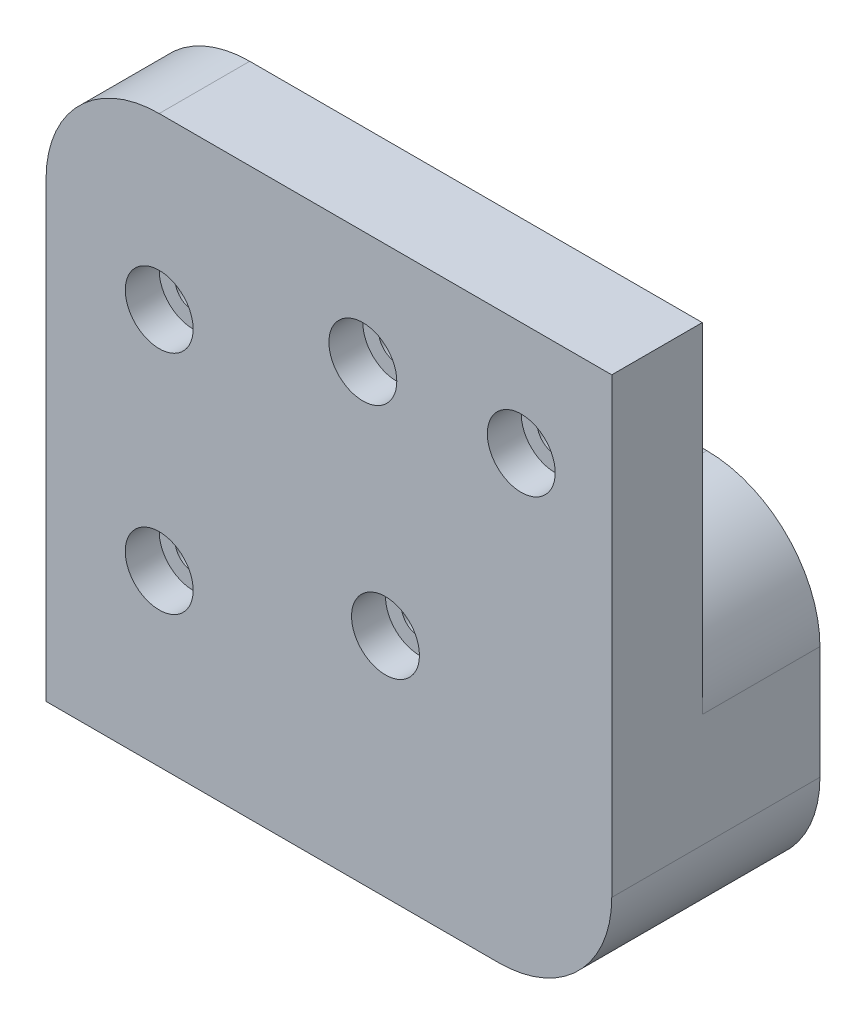
SolidWorks part; units mm, degrees
ref_plane "前视基准面" through (0, 0, 0) normal (0, 0, 1) x (1, 0, 0)
ref_plane "上视基准面" through (0, 0, 0) normal (0, 1, 0) x (1, 0, 0)
ref_plane "右视基准面" through (0, 0, 0) normal (1, 0, 0) x (0, 0, -1)
other "Configuration Table"
sketch "草图1" plane through (0, 0, 0) normal (0, 0, 1) x (1, 0, 0)
  line L0 (-10, 77.5) -> (-10, -160) construction
  line L2 (10, 57.5) -> (10, 27.5)
  line L3 (10, 27.5) -> (-10, 27.5)
  line L4 (-10, 77.5) -> (-10, 27.5)
  line L5 (-10, 77.5) -> (40, 77.5)
  line L7 (10, 57.5) -> (40, 57.5)
  line L8 (40, 77.5) -> (40, 57.5)
  line L9 (184.3942, 77.5) -> (10.0042, 77.5) construction
  line L10 (184.3942, 57.5) -> (10.0042, 57.5) construction
  line L11 (10, -130.0288) -> (10, 47.5288) construction
  circle A0 centre (32, 67.5) radius 1.6
  circle A1 centre (18, 67.5) radius 1.6
  circle A2 centre (0, 62.5) radius 1.6
  circle A3 centre (0, 42.5) radius 1.6
  point P22 (0, 27.5)
  point P23 (40, 67.5)
  dimension "D2" = 3.2
  dimension "D1" = 50
  dimension "D3" = 8
  dimension "D4" = 8
  dimension "D5" = 15
  dimension "D6" = 15
extrude "凸台-拉伸1" add sketch "草图1" along normal blind 8
sketch "草图2" plane through (0, 0, 8) normal (0, 0, 1) x (1, 0, 0)
  circle A0 centre (32, 67.5) radius 3
  circle A1 centre (0, 42.5) radius 1.6
  circle A2 centre (0, 42.5) radius 1.6 construction
  circle A3 centre (0, 62.5) radius 1.6
  circle A4 centre (0, 62.5) radius 1.6 construction
  circle A5 centre (18, 67.5) radius 1.6
  circle A6 centre (18, 67.5) radius 1.6 construction
  circle A7 centre (32, 67.5) radius 1.6
  circle A8 centre (32, 67.5) radius 1.6 construction
  circle A9 centre (18, 67.5) radius 3
  circle A10 centre (0, 62.5) radius 3
  circle A11 centre (0, 42.5) radius 3
  dimension "D1" = 6
  dimension "D2" = 0
  dimension "D3" = 0
  dimension "D4" = 0
  dimension "D5" = 0
extrude "切除-拉伸1" cut sketch "草图2" against normal blind 3
fillet "圆角1" radius 10 2 edges at (10, 57.5, 4) (-10, 77.5, 4)
sketch "草图3" plane through (0, 0, 8) normal (0, 0, 1) x (1, 0, 0)
  line L0 (40, 57.5) -> (40, 27.5)
  line L2 (40, 27.5) -> (10, 27.5)
  line L3 (10, 27.5) -> (10, 47.5) construction
  line L4 (20, 57.5) -> (40, 57.5) construction
  line L5 (10, 27.5) -> (10, 47.5)
  line L6 (20, 57.5) -> (40, 57.5)
  line L7 (-10, 27.5) -> (10, 27.5) construction
  arc A0 (20, 57.5288) -> (10, 47.5288) centre (20, 47.5288) ccw construction
  arc A1 (20, 57.5288) -> (10, 47.5288) centre (20, 47.5288) ccw
  circle A2 centre (20, 47.5288) radius 2.05 construction
  circle A3 centre (20, 47.5288) radius 2.05 construction
  circle A4 centre (20, 47.5288) radius 1.6
  line M10 (10, 27.5) -> (10, 47.5)
  arc M11 (10, 47.5) -> (20, 57.5) centre (20, 47.5) cw
  line M12 (20, 57.5) -> (40, 57.5)
  dimension "D1" = 3.2
extrude "凸台-拉伸2" add sketch "草图3" against normal up to surface (18.3999 mm away) contours L2 L0 M12 M11 M10
sketch "草图5" plane through (0, 0, 8) normal (0, 0, 1) x (1, 0, 0)
  circle A0 centre (20, 47.5288) radius 1.6 construction
  circle A1 centre (20, 47.5288) radius 1.6 construction
  circle A2 centre (20, 47.5288) radius 3
  dimension "D1" = 6
extrude "切除-拉伸2" cut sketch "草图5" against normal blind 3
fillet "圆角2" radius 10 3 edges at (10, 27.5, -5.2) (40, 57.5, -5.2) (40, 27.5, -1.2)
